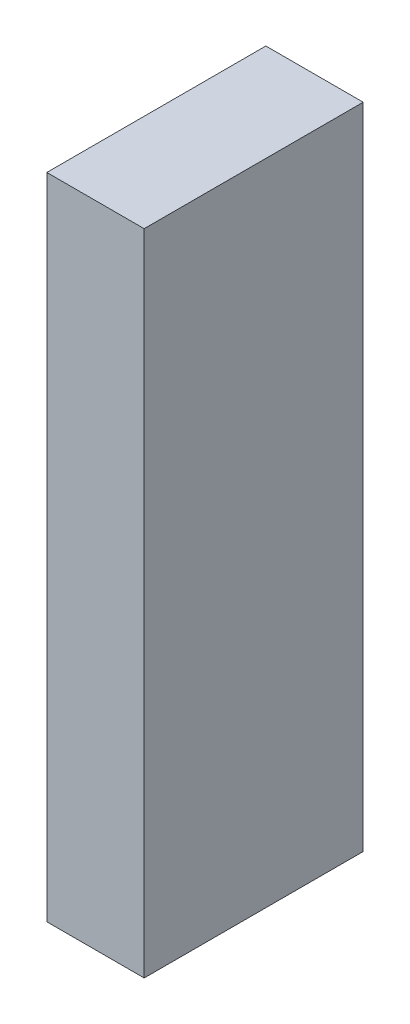
SolidWorks part; units mm, degrees
ref_plane "Top" through (0, 0, 0) normal (0, 0, 1) x (1, 0, 0)
ref_plane "Front" through (0, 0, 0) normal (0, 1, 0) x (1, 0, 0)
ref_plane "Right" through (0, 0, 0) normal (1, 0, 0) x (0, 0, -1)
sketch "Profile Sketch" plane through (-13.8341, 0, -105.7567) normal (0, 1, 0) x (-1, 0, 0)
  line L1 (-3, 0) -> (3, 0)
  line L2 (-3, 0) -> (-3, 13.5)
  line L3 (-3, 13.5) -> (3, 13.5)
  line L4 (3, 0) -> (3, 13.5)
  line L5 (0, 13.5) -> (0, 0) construction
  line L6 (-3, 6.75) -> (3, 6.75) construction
  point P128 (0, 6.75)
  dimension "Height" = 13.5
  dimension "Width" = 6
extrude "Profile Extrude" add sketch "Profile Sketch" along normal blind 40
